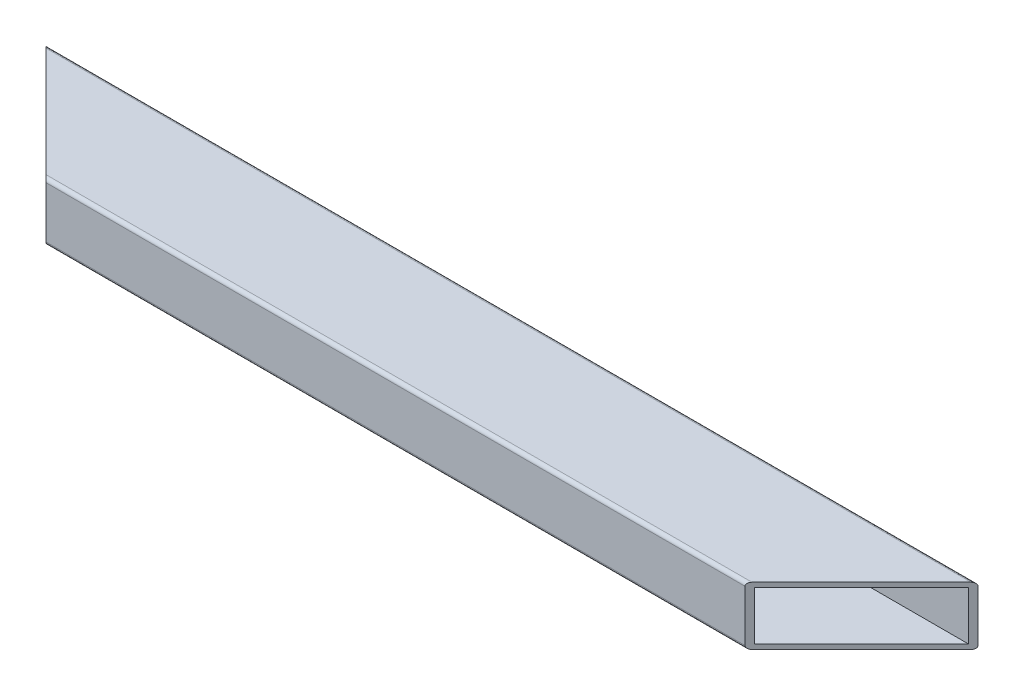
SolidWorks part; units mm, degrees
ref_plane "Front Plane" through (0, 0, 0) normal (0, 0, 1) x (1, 0, 0)
ref_plane "Top Plane" through (0, 0, 0) normal (0, 1, 0) x (1, 0, 0)
ref_plane "Right Plane" through (0, 0, 0) normal (1, 0, 0) x (0, 0, -1)
sketch "Sketch1" plane through (0, 0, 0) normal (1, 0, 0) x (0, 0, -1)
  line L1 (-23.5, 12.5) -> (23.5, 12.5)
  line L2 (-25, 11) -> (-25, -11)
  line L3 (-23.5, -12.5) -> (23.5, -12.5)
  line L4 (25, 11) -> (25, -11)
  line L5 (-25, 12.5) -> (25, -12.5) construction
  line L6 (-25, -12.5) -> (25, 12.5) construction
  arc A0 (-23.5, -12.5) -> (-25, -11) centre (-23.5, -11) cw
  arc A1 (23.5, -12.5) -> (25, -11) centre (23.5, -11) ccw
  arc A2 (25, 11) -> (23.5, 12.5) centre (23.5, 11) ccw
  arc A3 (-25, 11) -> (-23.5, 12.5) centre (-23.5, 11) cw
  point P0 (0, 0)
  dimension "D3" = 1.5
  dimension "D1" = 50
  dimension "D2" = 25
extrude "Boss-Extrude1" add sketch "Sketch1" along normal mid plane 1524
shell "Shell1" thickness 2
sketch "Sketch2" plane through (0, 12.5, 0) normal (0, 1, 0) x (1, 0, 0)
  line L0 (-200, 25) -> (-150, -25)
  line L1 (762, 25) -> (-762, 25) construction
  line L2 (762, -25) -> (-762, -25) construction
  line L4 (0, -13.75) -> (0, 13.75) construction
  line L5 (200, 25) -> (150, -25)
  point P6 (0, 0)
  dimension "D1" = 45
  dimension "D2" = 400
ref_plane "Plane1" through (-87.5, 0, 87.5) normal (-0.7071, 0, 0.7071) x (0.7071, 0, 0.7071)
other "SurfaceCut1"
ref_plane "Plane2" through (87.5, 0, 87.5) normal (-0.7071, 0, -0.7071) x (-0.7071, 0, 0.7071)
other "SurfaceCut2"
